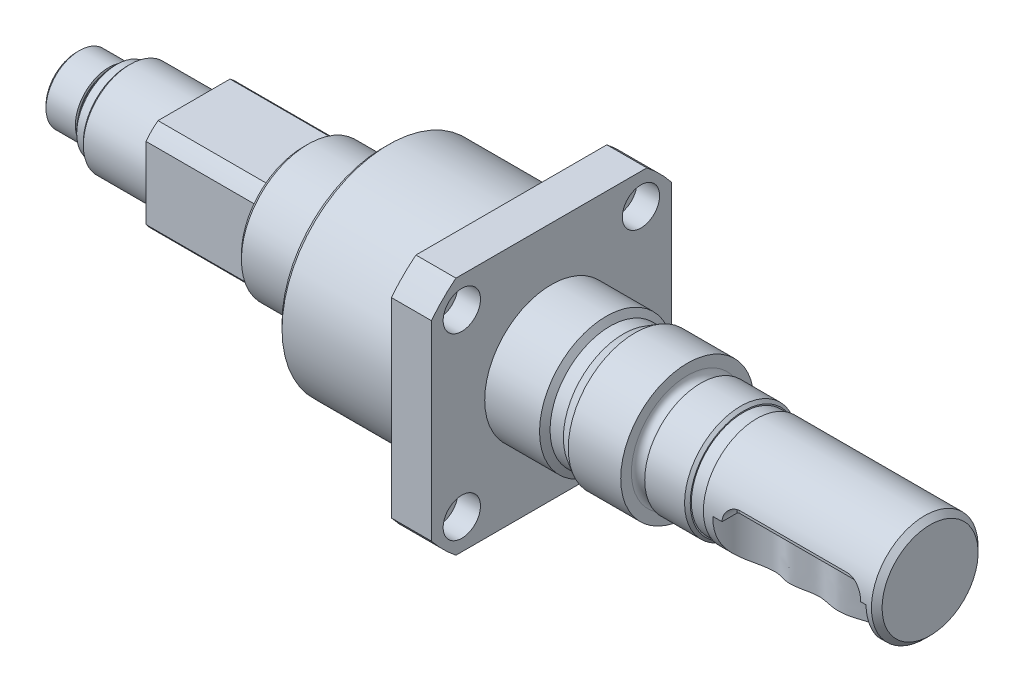
SolidWorks part; units mm, degrees
ref_plane "Front Plane" through (0, 0, 0) normal (0, 0, 1) x (1, 0, 0)
ref_plane "Top Plane" through (0, 0, 0) normal (0, 1, 0) x (1, 0, 0)
ref_plane "Right Plane" through (0, 0, 0) normal (1, 0, 0) x (0, 0, -1)
sketch "Sketch1" plane through (0, 0, 0) normal (0, 0, 1) x (1, 0, 0)
  line L0 (-674.9165, 0) -> (33070.9099, 0) construction
  line L1 (0, -674.9165) -> (0, 33070.9099) construction
  line L2 (0, 40) -> (0, 0)
  line L3 (0, 40) -> (24, 40)
  line L4 (61, 22.5) -> (66, 22.5)
  line L5 (59.5566, 25) -> (61, 22.5)
  line L6 (24, 40) -> (24, 45)
  line L7 (24, 45) -> (39, 45)
  line L8 (39, 45) -> (39, 25)
  line L9 (39, 25) -> (59.5566, 25)
  line L10 (66, 22.5) -> (70.3301, 25)
  line L11 (70.3301, 25) -> (90, 25)
  line L12 (95, 21) -> (109.9393, 21)
  line L13 (90, 25) -> (90, 21)
  line L14 (109.9393, 21) -> (111, 19.9393)
  line L15 (111, 19.9393) -> (111, 19.5)
  line L16 (111, 19.5) -> (116, 19.5)
  line L17 (116, 19.5) -> (116, 20)
  line L18 (116, 20) -> (179, 20)
  line L19 (179, 20) -> (181, 18)
  line L20 (181, 18) -> (181, 0)
  line L21 (61, 22.5) -> (61, 25) construction
  line L22 (66, 22.5) -> (66, 25) construction
  line L23 (0, 40) -> (-22, 40)
  line L24 (-22, 40) -> (-24, 38)
  line L25 (-52.2322, 25) -> (-29, 25)
  line L26 (-24, 38) -> (-24, 25)
  line L27 (-52.2322, 25) -> (-54, 23.2322)
  line L28 (-95, 18) -> (-54, 18)
  line L29 (-54, 23.2322) -> (-54, 18)
  line L30 (-120, 17.5) -> (-95, 17.5)
  line L31 (-95, 18) -> (-95, 17.5)
  line L32 (-120, 17.5) -> (-120, 15)
  line L33 (-120, 15) -> (-125, 15)
  line L34 (-125, 15) -> (-125, 11.5)
  line L35 (-125, 11.5) -> (-127, 11.5)
  line L36 (-127, 11.5) -> (-127, 12.5)
  line L37 (-127, 12.5) -> (-139, 12.5)
  line L38 (-139, 12.5) -> (-139, 0)
  line L39 (-139, 0) -> (181, 0)
  arc A0 (90, 21) -> (95, 21) centre (92.5, 21) ccw
  arc A1 (-29, 25) -> (-24, 25) centre (-26.5, 25) ccw
  point P46 (-122.5, 15)
  point P48 (-120, 16.25)
  dimension "D12" = 2.5
  dimension "D28" = 5
  dimension "D1" = 40
  dimension "D2" = 24
  dimension "D3" = 15
  dimension "D4" = 45
  dimension "D5" = 25
  dimension "D6" = 22.5
  dimension "D7" = 30
  dimension "D8" = 5
  dimension "D9" = 60
  dimension "D10" = 25
  dimension "D11" = 21
  dimension "D13" = 1.5
  dimension "D14" = 135
  dimension "D15" = 5
  dimension "D16" = 70
  dimension "D17" = 19.5
  dimension "D18" = 2
  dimension "D19" = 135
  dimension "D20" = 20
  dimension "D21" = 115
  dimension "D22" = 91
  dimension "D23" = 22
  dimension "D24" = 22
  dimension "D25" = 135
  dimension "D26" = 2
  dimension "D27" = 25
  dimension "D29" = 2.5
  dimension "D30" = 18
  dimension "D31" = 85
  dimension "D32" = 17.5
  dimension "D33" = 15
  dimension "D34" = 12.5
  dimension "D35" = 44
  dimension "D36" = 19
  dimension "D37" = 12
  dimension "D38" = 320
  dimension "D39" = 2
  dimension "D40" = 1
revolve "Revolve4" add sketch "Sketch1" angle 360 about L0
sketch "Sketch2" plane through (0, 0, 0) normal (0, 1, 0) x (1, 0, 0)
  line L0 (-139, 12.5) -> (-139, 11.5)
  line L1 (-139, 12.5) -> (-139, -12.5) construction
  line L2 (-139, 11.5) -> (-138, 12.5)
  line L3 (-127, 12.5) -> (-139, 12.5) construction
  line L4 (-138, 12.5) -> (-139, 12.5)
  line L5 (-125, 15) -> (-124, 15)
  line L6 (-124, 15) -> (-125, 14)
  line L7 (-125, 15) -> (-125, -15) construction
  line L8 (-125, 14) -> (-125, 15)
  line L9 (-120, 17.5) -> (-119, 17.5)
  line L10 (-119, 17.5) -> (-120, 16.5)
  line L11 (-120, 17.5) -> (-120, -17.5) construction
  line L12 (-120, 16.5) -> (-120, 17.5)
  line L13 (-139, 0) -> (-140.5222, 0) construction
  dimension "D1" = 1
  dimension "D2" = 1
  dimension "D3" = 1
  dimension "D4" = 1
  dimension "D5" = 1
revolve "Cut-Revolve1" cut sketch "Sketch2" angle 360 about L13
sketch3d "3DSketch1"
  point P0 (0, 0, 0)
ref_plane "Plane2" through (-95, 0, 0) normal (-1, 0, 0) x (0, 0, 1)
sketch "Sketch4" plane through (-95, 0, 0) normal (-1, 0, 0) x (0, 0, 1)
  line L1 (-18, -18) -> (18, -18)
  line L2 (-18, -18) -> (-18, 18)
  line L3 (-18, 18) -> (18, 18)
  line L4 (18, -18) -> (18, 18)
  line L5 (-18, -18) -> (18, 18) construction
  line L6 (-18, 18) -> (18, -18) construction
  circle A0 centre (0, 0) radius 22.5
  point P0 (0, 0)
  dimension "D3" = 45
  dimension "D1" = 36
  dimension "D2" = 36
extrude "Boss-Extrude2" add sketch "Sketch4" against normal up to surface (41 mm away) contours L4 A0 L3 L2 L1
ref_plane "Plane3" through (24, 0, 0) normal (-1, 0, 0) x (0, 0, 1)
sketch "Sketch5" plane through (24, 0, 0) normal (-1, 0, 0) x (0, 0, 1)
  line L1 (-45, -45) -> (45, -45)
  line L2 (-45, -45) -> (-45, 45)
  line L3 (-45, 45) -> (45, 45)
  line L4 (45, -45) -> (45, 45)
  line L5 (-45, -45) -> (45, 45) construction
  line L6 (-45, 45) -> (45, -45) construction
  circle A0 centre (0, 0) radius 57.5
  point P0 (0, 0)
  dimension "D3" = 115
  dimension "D1" = 90
  dimension "D2" = 90
extrude "Boss-Extrude3" add sketch "Sketch5" against normal blind 15 contours L4 A0 L3 L2 L1
sketch "Sketch6" plane through (39, 0, 0) normal (1, 0, 0) x (0, 0, -1)
  line L0 (0, 0) -> (47.5, 0) construction
  line L1 (0, 0) -> (33.5876, -33.5876) construction
  circle A0 centre (0, 0) radius 47.5
  circle A1 centre (33.5876, -33.5876) radius 7
  circle A2 centre (-33.5876, -33.5876) radius 7
  circle A3 centre (-33.5876, 33.5876) radius 7
  circle A4 centre (33.5876, 33.5876) radius 7
  point P15 (0, 0)
  dimension "D1" = 95
  dimension "D3" = 14
  dimension "D2" = 45
  dimension "D4" = 4
extrude "Cut-Extrude1" cut sketch "Sketch6" against normal blind 8.5 contours A0 A3 | A0 A3 | A0 A4 | A0 A4 | A0 A1 | A0 A1 | A0 A2 | A0 A2
sketch "Sketch7" plane through (30.5, 0, 0) normal (1, 0, 0) x (0, 0, -1)
  circle A0 centre (-33.5876, -33.5876) radius 7 construction
  circle A1 centre (33.5876, -33.5876) radius 7 construction
  circle A2 centre (33.5876, 33.5876) radius 7 construction
  circle A3 centre (-33.5876, 33.5876) radius 7 construction
  circle A4 centre (-33.5876, -33.5876) radius 7
  circle A5 centre (33.5876, -33.5876) radius 7
  circle A6 centre (33.5876, 33.5876) radius 7
  circle A7 centre (-33.5876, 33.5876) radius 7
  circle A8 centre (-33.5876, 33.5876) radius 4.5
  circle A9 centre (33.5876, 33.5876) radius 4.5
  circle A10 centre (33.5876, -33.5876) radius 4.5
  circle A11 centre (-33.5876, -33.5876) radius 4.5
  point P23 (0, 0)
  dimension "D1" = 2.5
  dimension "D2" = 4
extrude "Cut-Extrude3" cut sketch "Sketch7" against normal through all contours A8 | A9 | A10 | A11
sketch "Sketch8" plane through (0, 0, 0) normal (0, 0, 1) x (1, 0, 0)
  line L0 (181, 0) -> (116, 0) construction
  line L1 (181, -18) -> (181, 18) construction
  line L2 (116, 20) -> (116, -20) construction
  line L3 (129, 0) -> (169, 0) construction
  line L4 (129, 6) -> (169, 6)
  line L5 (129, -6) -> (169, -6)
  arc A0 (129, 6) -> (129, -6) centre (129, 0) ccw
  arc A1 (169, -6) -> (169, 6) centre (169, 0) ccw
  point P8 (149, 0)
  point P13 (175, 0)
  point P14 (123, 0)
  dimension "D1" = 12
  dimension "D2" = 52
  dimension "D3" = 6
extrude "Cut-Extrude4" cut sketch "Sketch8" against normal blind 6 from offset 20
fillet "Fillet1" radius 0.5 4 edges at (175, 0, 14) (149, -6, 14) (123, 0, 14) (149, 6, 14)
sketch "Sketch9" plane through (0, 0, 0) normal (0, 1, 0) x (1, 0, 0)
  line L5 (0, 0) -> (11.1003, 0) construction
  line L11 (22, 40.8056) -> (24, 40.8056)
  line L12 (24, 40) -> (24, -40) construction
  line L13 (24, 40.8056) -> (24, 38.8056)
  line L14 (24, 45) -> (24, 35.7946) construction
  line L15 (24, 38.8056) -> (22, 38.8056)
  line L16 (22, 38.8056) -> (22, 40.8056)
  dimension "D1" = 2
  dimension "D2" = 2
  dimension "D3" = 38.8056
revolve "Cut-Revolve4" cut sketch "Sketch9" angle 360 about L5
sketch "Sketch10" plane through (0, 0, 0) normal (0, 1, 0) x (1, 0, 0)
  line L0 (116, -20) -> (123, -20) construction
  line L1 (175, -20) -> (179, -20) construction
  spline S0 degree 3 poles (192.6844, -42.3789) (111.8239, -37.4388) (121.9784, -10.6596) (131.2686, -6.2798) (138.9562, -11.9509) (146.9517, -4.9973) (157.4666, -13.1686) (169.6787, 1.7348) (192.6844, -42.3789) (111.8239, -37.4388) (121.9784, -10.6596) knots -0.662068 -0.573001 -0.436204 0 0.063997 0.145816 0.191702 0.254001 0.337932 0.426999 0.563796 1 1.063997 1.145816 1.191702 only from (119.5, -20) to (119.5, -20)
extrude "Cut-Extrude5" cut sketch "Sketch10" against normal blind 67
